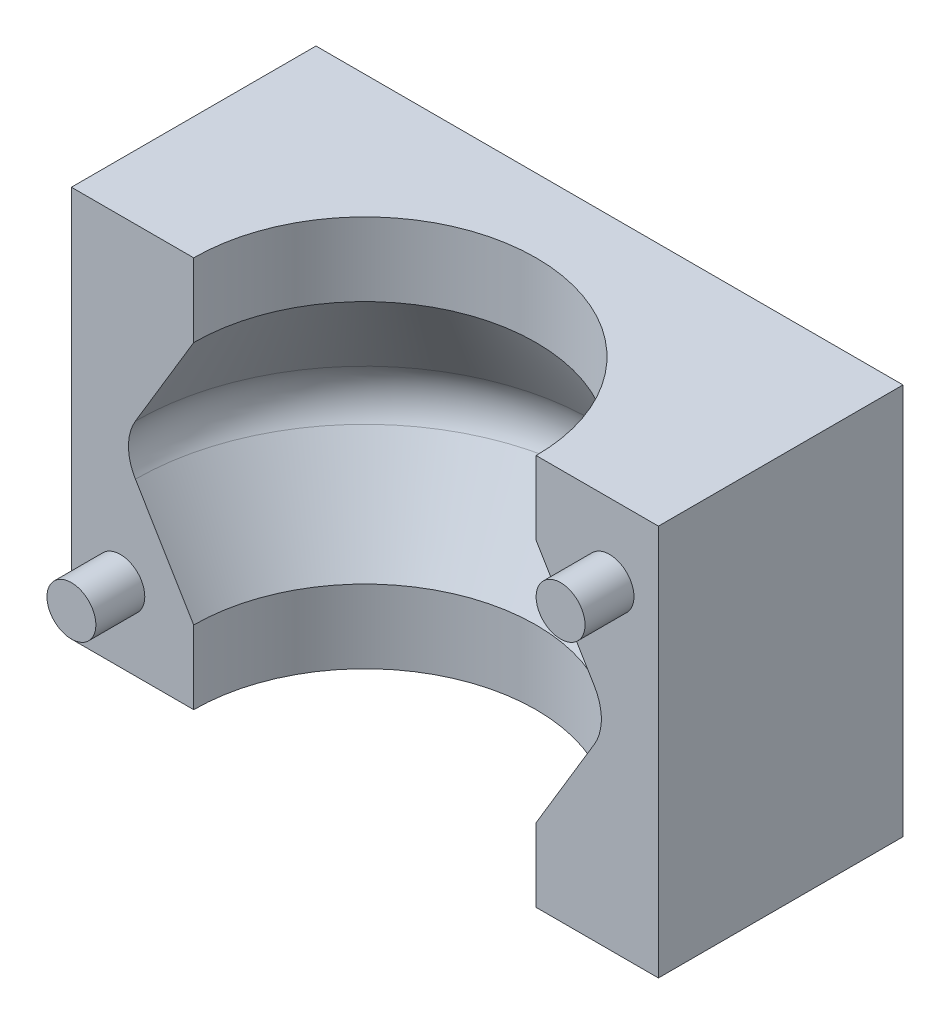
SolidWorks part; units mm, degrees
ref_plane "Front Plane" through (0, 0, 0) normal (0, 0, 1) x (1, 0, 0)
ref_plane "Top Plane" through (0, 0, 0) normal (0, 1, 0) x (1, 0, 0)
ref_plane "Right Plane" through (0, 0, 0) normal (1, 0, 0) x (0, 0, -1)
sketch "Sketch1" plane through (0, 0, 0) normal (0, 0, 1) x (1, 0, 0)
  line L1 (60, -40) -> (-60, -40)
  line L2 (60, -40) -> (60, 40)
  line L3 (60, 40) -> (-60, 40)
  line L4 (-60, -40) -> (-60, 40)
  line L5 (60, -40) -> (-60, 40) construction
  line L6 (60, 40) -> (-60, -40) construction
  point P0 (0, 0)
  dimension "D1" = 120
  dimension "D2" = 80
extrude "Boss-Extrude1" add sketch "Sketch1" along normal blind 50
sketch "Sketch2" plane through (0, 0, 50) normal (0, 0, 1) x (1, 0, 0)
  line L0 (0, 43.9271) -> (0, -46.1107) construction
  line L1 (-67.3036, 0) -> (76.5514, 0) construction
  line L2 (-35, 40) -> (-35, 25)
  line L3 (60, 40) -> (-60, 40) construction
  line L4 (-35, 25) -> (-46.913, 5.145)
  line L5 (-35, -25) -> (-46.913, -5.145)
  line L6 (-35, -40) -> (-35, -25)
  line L7 (-35, -40) -> (0, -40)
  line L8 (-60, -40) -> (60, -40) construction
  line L9 (-35, 40) -> (0, 40)
  line L10 (0, -40) -> (0, 40)
  arc A0 (-46.913, 5.145) -> (-46.913, -5.145) centre (-38.3381, 0) ccw
  point P18 (-50, 0)
  dimension "D4" = 10
  dimension "D1" = 35
  dimension "D2" = 50
  dimension "D3" = 15
sketch "Sketch3" plane through (0, 0, 50) normal (0, 0, 1) x (1, 0, 0)
  line L0 (0, 43.1565) -> (0, -38.2757) construction
  line L1 (-69.1018, 0) -> (69.2302, 0) construction
  circle A0 centre (50, 25) radius 5
  circle A2 centre (-50, -25) radius 5
  dimension "D1" = 10
  dimension "D2" = 25
  dimension "D3" = 50
extrude "Boss-Extrude2" add sketch "Sketch3" along normal blind 10
revolve "Cut-Revolve2" cut sketch "Sketch2" angle 360 about L0
sketch "Sketch4" plane through (0, 40, 0) normal (0, 1, 0) x (1, 0, 0)
  line L0 (0, 11.6357) -> (0, -56.9523) construction
  line L1 (-5.1, -13.1513) -> (-5.1, -15.3736)
  line L2 (5.1, -13.1513) -> (5.1, -15.3736)
  arc A0 (35, -50) -> (-35, -50) centre (0, -50) ccw construction
  arc A1 (5.1, -15.3736) -> (-5.1, -15.3736) centre (0, -50) ccw
  arc A2 (5.1, -13.1513) -> (-5.1, -13.1513) centre (0, -50) ccw
  arc A4 (37.2, -50) -> (-37.2, -50) centre (0, -50) ccw construction
  arc A5 (35, -50) -> (-35, -50) centre (0, -50) ccw construction
  dimension "D2" = 5.1
  dimension "D1" = 2.2
